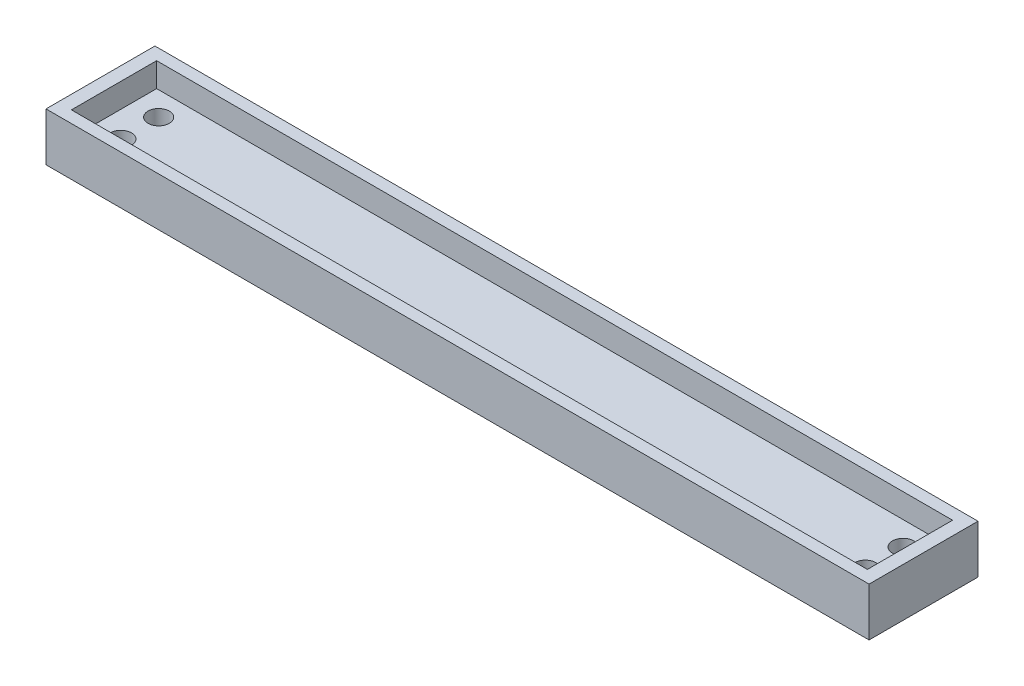
SolidWorks part; units mm, degrees
ref_plane "Front Plane" through (0, 0, 0) normal (0, 0, 1) x (1, 0, 0)
ref_plane "Top Plane" through (0, 0, 0) normal (0, 1, 0) x (1, 0, 0)
ref_plane "Right Plane" through (0, 0, 0) normal (1, 0, 0) x (0, 0, -1)
sketch "Sketch1" plane through (0, 0, 0) normal (0, 1, 0) x (1, 0, 0)
  line L1 (0, 0) -> (215.9, 0)
  line L2 (0, 0) -> (0, 28.575)
  line L3 (0, 28.575) -> (215.9, 28.575)
  line L4 (215.9, 0) -> (215.9, 28.575)
  dimension "D1" = 215.9
  dimension "D2" = 28.575
extrude "Boss-Extrude1" add sketch "Sketch1" along normal blind 12.7
sketch "Sketch2" plane through (0, 12.7, 0) normal (0, 1, 0) x (1, 0, 0)
  line L0 (0, 14.2875) -> (215.9, 14.2875) construction
  line L1 (0, 28.575) -> (0, 0) construction
  line L2 (215.9, 0) -> (215.9, 28.575) construction
  line L3 (107.95, 28.575) -> (107.95, 0) construction
  line L4 (215.9, 28.575) -> (0, 28.575) construction
  line L5 (0, 0) -> (215.9, 0) construction
  line L7 (3.556, 25.4635) -> (212.344, 25.4635)
  line L8 (3.556, 25.4635) -> (3.556, 3.1115)
  line L9 (3.556, 3.1115) -> (212.344, 3.1115)
  line L10 (212.344, 25.4635) -> (212.344, 3.1115)
  point P16 (107.95, 25.4635)
  point P17 (212.344, 14.2875)
  dimension "D1" = 208.788
  dimension "D2" = 22.352
extrude "Cut-Extrude1" cut sketch "Sketch2" against normal blind 6.35
sketch "Sketch4" plane through (0, 6.35, 0) normal (0, 1, 0) x (1, 0, 0)
  line L0 (3.556, 14.2875) -> (212.344, 14.2875) construction
  line L1 (3.556, 25.4635) -> (3.556, 3.1115) construction
  line L2 (212.344, 3.1115) -> (212.344, 25.4635) construction
  line L3 (107.95, 25.4635) -> (107.95, 3.1115) construction
  line L4 (212.344, 25.4635) -> (3.556, 25.4635) construction
  line L5 (3.556, 3.1115) -> (212.344, 3.1115) construction
  circle A0 centre (10.3124, 19.2405) radius 2.794
  circle A1 centre (10.3124, 9.3345) radius 2.794
  circle A2 centre (205.5876, 9.3345) radius 2.794
  circle A3 centre (205.5876, 19.2405) radius 2.794
  dimension "D1" = 5.588
  dimension "D2" = 97.6376
  dimension "D3" = 4.953
extrude "Cut-Extrude2" cut sketch "Sketch4" against normal through all
